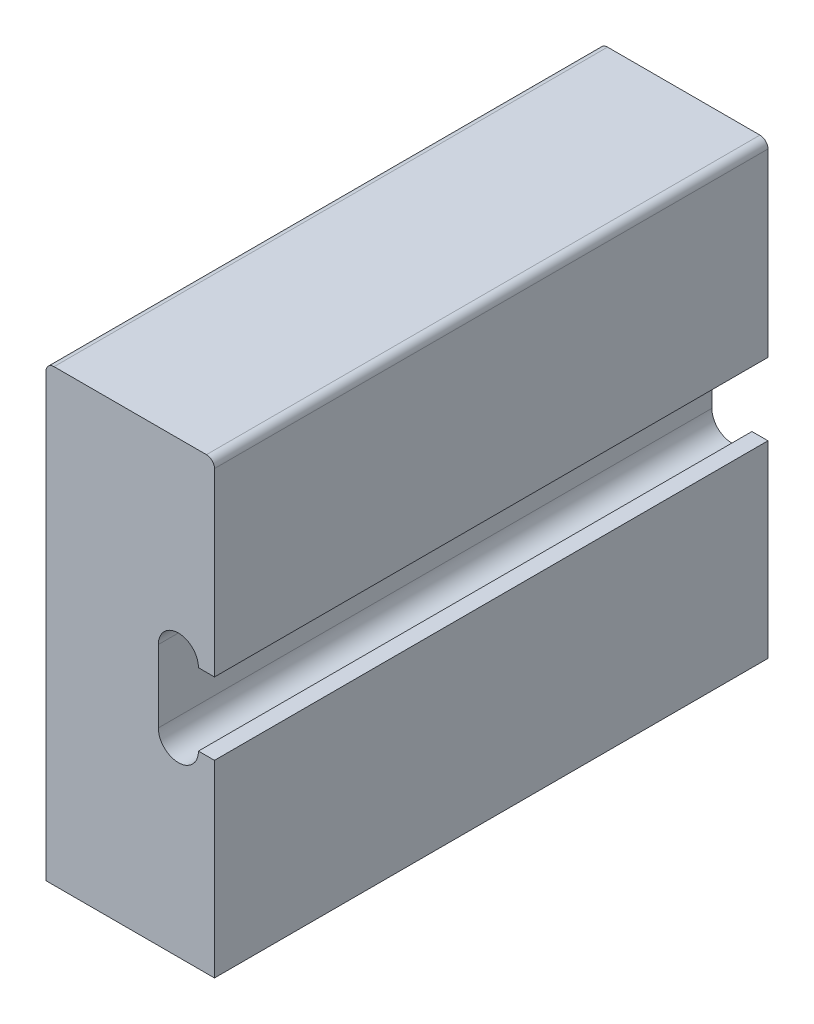
SolidWorks part; units mm, degrees
ref_plane "Front Plane" through (0, 0, 0) normal (0, 0, 1) x (1, 0, 0)
ref_plane "Top Plane" through (0, 0, 0) normal (0, 1, 0) x (1, 0, 0)
ref_plane "Right Plane" through (0, 0, 0) normal (1, 0, 0) x (0, 0, -1)
sketch "Sketch1" plane through (0, 0, 0) normal (1, 0, 0) x (0, 0, -1)
  line L1 (-34.5, 0) -> (-34.5, 28)
  line L2 (-34.5, 28) -> (34.5, 28)
  line L3 (34.5, 28) -> (34.5, -28)
  line L4 (34.5, -28) -> (-34.5, -28)
  line L5 (-34.5, -28) -> (-34.5, 0)
extrude "Boss-Extrude1" add sketch "Sketch1" along normal blind 21
fillet "Fillet1" radius 1 2 edges at (0, 28, 0) (21, 28, 0)
sketch "Sketch2" plane through (0, 0, -34.5) normal (0, 0, -1) x (-1, 0, 0)
  line L1 (-21, -28) -> (-21, 27) construction
  line L2 (-21, -4.5) -> (-19, -4.5)
  line L3 (-21, 4.5) -> (-21, -4.5)
  line L5 (-14, -4.5) -> (-14, 4.5)
  line L8 (-19, 4.5) -> (-21, 4.5)
  arc A0 (-14, 4.5) -> (-19, 4.5) centre (-16.5, 4.5) ccw
  arc A1 (-19, -4.5) -> (-14, -4.5) centre (-16.5, -4.5) ccw
extrude "Cut-Extrude1" cut sketch "Sketch2" against normal through all
